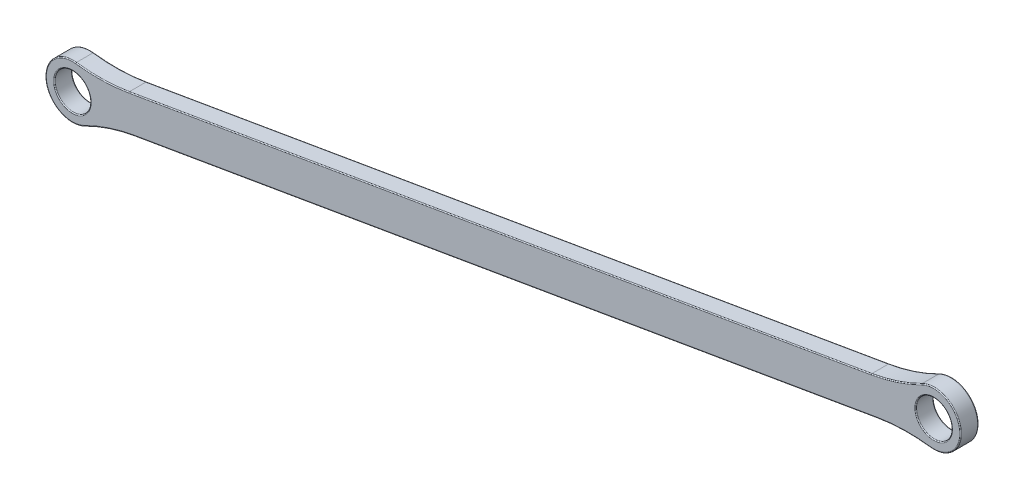
SolidWorks part; units mm, degrees
ref_plane "Front Plane" through (0, 0, 0) normal (0, 0, 1) x (1, 0, 0)
ref_plane "Top Plane" through (0, 0, 0) normal (0, 1, 0) x (1, 0, 0)
ref_plane "Right Plane" through (0, 0, 0) normal (1, 0, 0) x (0, 0, -1)
sketch "Sketch1" plane through (0, 0, 0) normal (0, 0, 1) x (1, 0, 0)
  line L0 (-100.3943, 222.5859) -> (-244.2998, 197.9445) construction
  line L1 (-100.3943, 222.5859) -> (-244.2998, 197.9445) construction
  line L2 (-244.2998, 197.9445) -> (-100.3943, 222.5859) construction
  line L3 (-244.8061, 200.9015) -> (-100.9006, 225.5429)
  line L4 (-243.7935, 194.9875) -> (-99.8879, 219.6289)
  arc A0 (-244.8061, 200.9015) -> (-243.7935, 194.9875) centre (-244.2998, 197.9445) ccw
  arc A1 (-99.8879, 219.6289) -> (-100.9006, 225.5429) centre (-100.3943, 222.5859) ccw
  circle A2 centre (-244.2998, 197.9445) radius 4.5
  circle A3 centre (-100.3943, 222.5859) radius 4.5
  arc A4 (-243.7935, 194.9875) -> (-244.8061, 200.9015) centre (-244.2998, 197.9445) ccw
  arc A5 (-100.9006, 225.5429) -> (-99.8879, 219.6289) centre (-100.3943, 222.5859) ccw
  point P2 (-172.347, 210.2652)
  dimension "D2" = 9
  dimension "D1" = 6
extrude "Boss-Extrude1" add sketch "Sketch1" against normal blind 3 contours A3 L3 A2 L4 | L3 A2 L4 A0 | A4 L4 A2 L3 | L4 A3 L3 A1 | A5 L3 A3 L4
fillet "Fillet2" radius 30 4 edges at (-240.4875, 195.5536, -1.5) (-103.1939, 219.0628, -1.5) (-104.2066, 224.9768, -1.5) (-241.5002, 201.4676, -1.5)
fillet "Fillet3" radius 0.15 20 edges at (-241.2998, 197.9445, -3) (-241.2998, 197.9445, 0) (-238.18, 195.6161, -3) (-238.18, 195.6161, 0) (-171.8407, 207.3082, 0) (-171.8407, 207.3082, -3) (-105.3908, 218.354, -3) (-105.3908, 218.354, 0) (-95.9588, 223.3454, 0) (-95.9588, 223.3454, -3) (-106.5141, 224.9143, -3) (-106.5141, 224.9143, 0) (-172.8534, 213.2222, 0) (-172.8534, 213.2222, -3) (-239.3033, 202.1764, -3) (-239.3033, 202.1764, 0) (-248.7353, 197.185, -3) (-248.7353, 197.185, 0) (-97.3943, 222.5859, -3) (-97.3943, 222.5859, 0)
